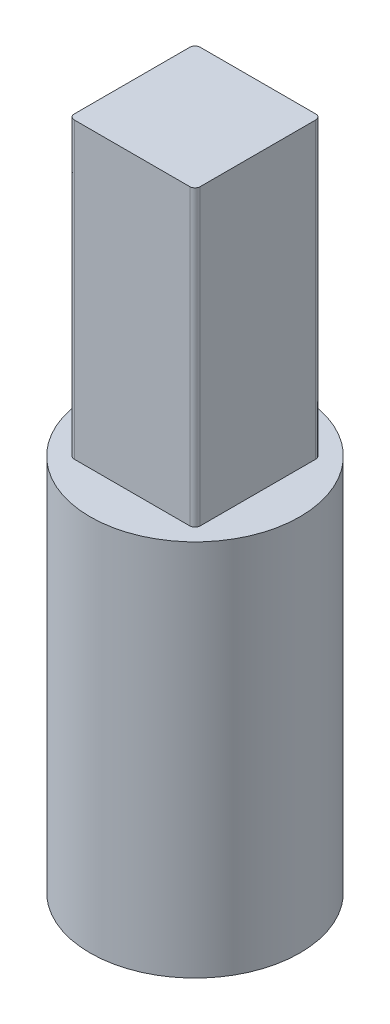
SolidWorks part; units mm, degrees
ref_plane "Front Plane" through (0, 0, 0) normal (0, 0, 1) x (1, 0, 0)
ref_plane "Top Plane" through (0, 0, 0) normal (0, 1, 0) x (1, 0, 0)
ref_plane "Right Plane" through (0, 0, 0) normal (1, 0, 0) x (0, 0, -1)
sketch "Sketch1" plane through (0, 0, 0) normal (0, 1, 0) x (1, 0, 0)
  line L1 (-76.2, 76.2) -> (76.2, 76.2)
  line L2 (-76.2, 76.2) -> (-76.2, -76.2)
  line L3 (-76.2, -76.2) -> (76.2, -76.2)
  line L4 (76.2, 76.2) -> (76.2, -76.2)
extrude "Boss-Extrude1" add sketch "Sketch1" along normal blind 355.6
fillet "Fillet1" radius 6.35 4 edges at (76.2, 177.8, -76.2) (76.2, 177.8, 76.2) (-76.2, 177.8, -76.2) (-76.2, 177.8, 76.2)
sketch "Sketch2" plane through (0, 0, 0) normal (0, -1, 0) x (-1, 0, 0)
  circle A0 centre (0, 0) radius 127
extrude "Boss-Extrude2" add sketch "Sketch2" along normal blind 457.2
